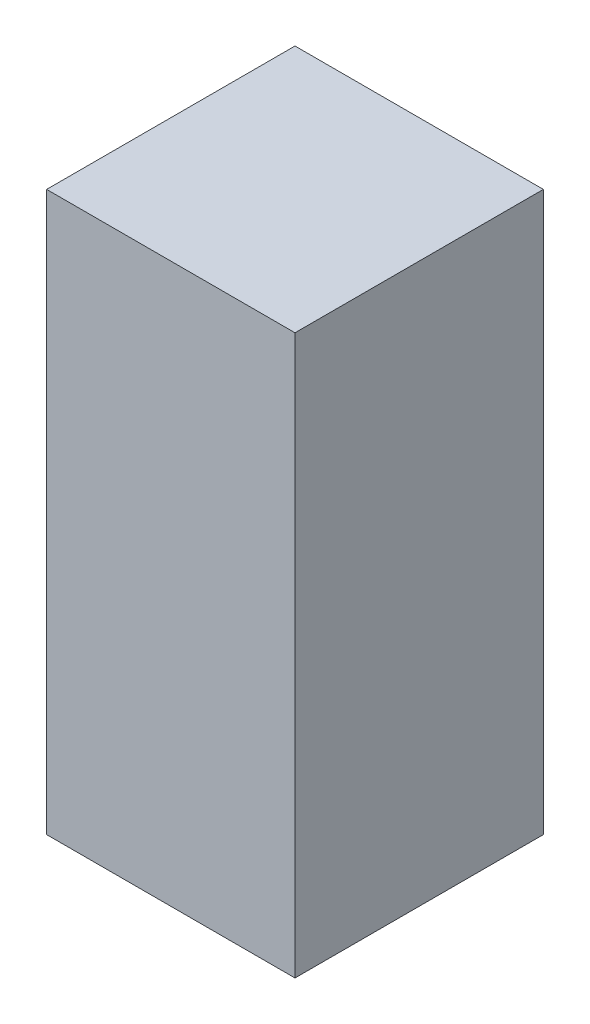
SolidWorks part; units mm, degrees
ref_plane "Front Plane" through (0, 0, 0) normal (0, 0, 1) x (1, 0, 0)
ref_plane "Top Plane" through (0, 0, 0) normal (0, 1, 0) x (1, 0, 0)
ref_plane "Right Plane" through (0, 0, 0) normal (1, 0, 0) x (0, 0, -1)
other "Configuration Table"
sketch "Sketch1" plane through (0, 0, 0) normal (0, 0, 1) x (1, 0, 0)
  line L1 (502.5, 552) -> (522.5, 552)
  line L2 (502.5, 552) -> (502.5, 597)
  line L3 (502.5, 597) -> (522.5, 597)
  line L4 (522.5, 552) -> (522.5, 597)
extrude "PACK_kose_plowu_4_1" add sketch "Sketch1" against normal blind 20 from offset 227.5 separate body
